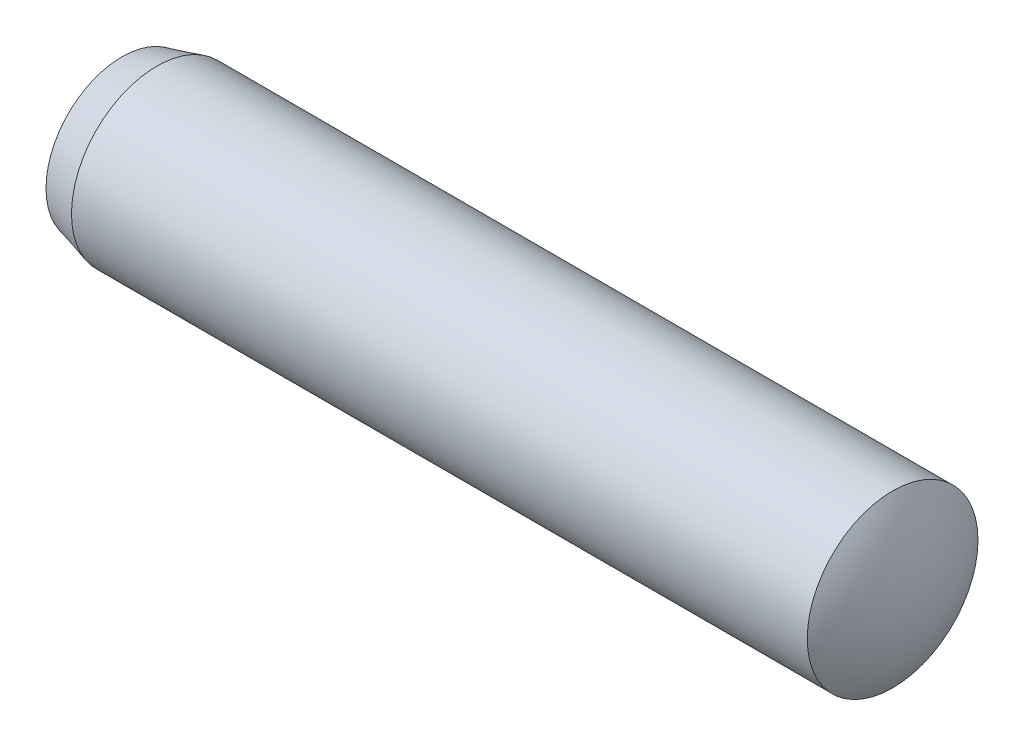
SolidWorks part; units mm, degrees
ref_plane "Front Plane" through (0, 0, 0) normal (0, 0, 1) x (1, 0, 0)
ref_plane "Top Plane" through (0, 0, 0) normal (0, 1, 0) x (1, 0, 0)
ref_plane "Right Plane" through (0, 0, 0) normal (1, 0, 0) x (0, 0, -1)
sketch "Sketch1" plane through (0, 0, 0) normal (1, 0, 0) x (0, 0, -1)
  line L1 (0, 2.5) -> (0, -2.5) construction
  circle A0 centre (0, 0) radius 2.5 construction
  point P4 (0, 0)
  dimension "Diameter" = 5
sketch "Sketch3" plane through (0, 0, 0) normal (0, 0, 1) x (1, 0, 0)
  line L0 (-12, 0) -> (12, 0)
  line L1 (12, 0) -> (12, 2.5)
  line L2 (12, 2.5) -> (-12, 2.5)
  line L3 (-12, 2.5) -> (-12, 0)
  line L4 (-10.3, 2.5) -> (-11.32, 2.2267)
  arc A0 (-11.32, 2.2267) -> (-12, 0) centre (-8.0143, 0) ccw
  arc A1 (12, 0) -> (11.25, 2.5) centre (7.4583, 0) ccw
  point P4 (0, 0)
  dimension "Length" = 24
  dimension "W" = 1.7
  dimension "D1" = 15
  dimension "D2" = 0.68
  dimension "C" = 0.75
sketch "Sketch5" plane through (0, 0, 0) normal (0, 0, 1) x (1, 0, 0)
  line L3 (-12, 0) -> (12, 0)
  line L4 (-10.3, 2.5) -> (-11.32, 2.2267) construction
  line L5 (-10.3, 2.5) -> (-11.32, 2.2267)
  line L6 (11.25, 2.5) -> (-10.3, 2.5)
  arc A2 (-11.32, 2.2267) -> (-12, 0) centre (-8.0143, 0) ccw construction
  arc A3 (12, 0) -> (11.25, 2.5) centre (7.4583, 0) ccw construction
  arc A4 (-11.32, 2.2267) -> (-12, 0) centre (-8.0143, 0) ccw
  arc A5 (12, 0) -> (11.25, 2.5) centre (7.4583, 0) ccw
revolve "Revolve1" add sketch "Sketch5" angle 360 about L0
equation "\"D2@Sketch3\"=\"W@Sketch3\"*.4"
